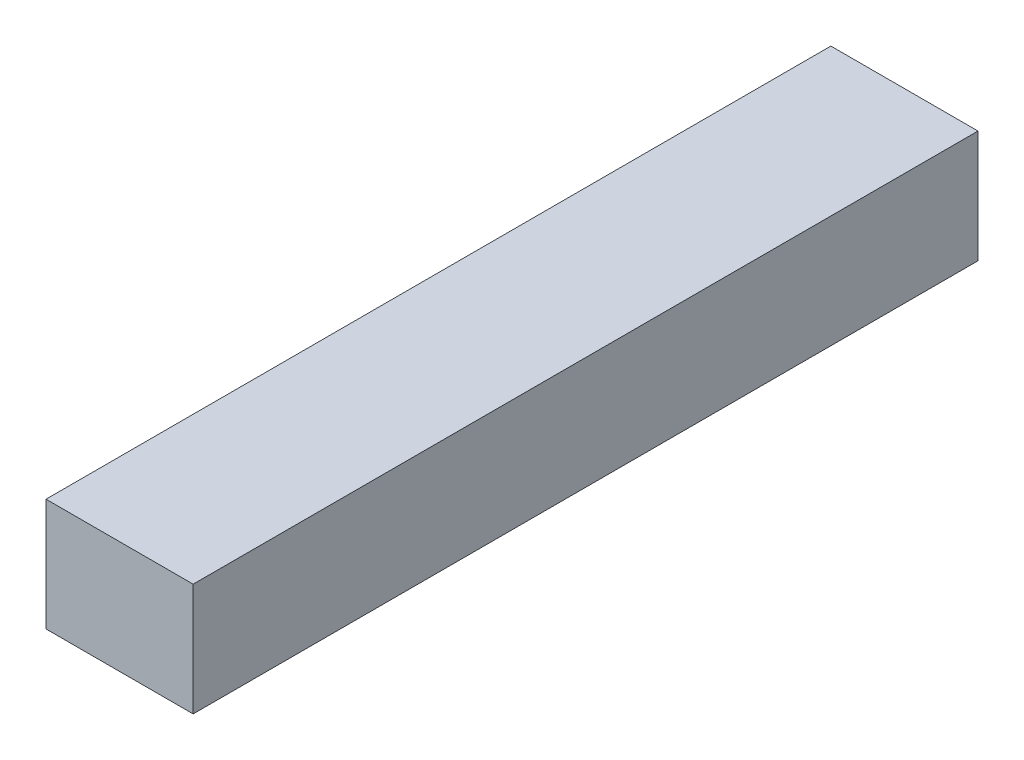
SolidWorks part; units mm, degrees
ref_plane "Front Plane" through (0, 0, 0) normal (0, 0, 1) x (1, 0, 0)
ref_plane "Top Plane" through (0, 0, 0) normal (0, 1, 0) x (1, 0, 0)
ref_plane "Right Plane" through (0, 0, 0) normal (1, 0, 0) x (0, 0, -1)
sketch "Sketch2" plane through (0, 0, 0) normal (0, 0, 1) x (1, 0, 0)
  line L0 (0, 0) -> (0, -4.583)
  line L1 (0, -4.583) -> (6, -4.583)
  line L2 (6, -4.583) -> (6, 0)
  line L3 (6, 0) -> (0, 0)
  dimension "D1" = 4.583
  dimension "D2" = 6
extrude "Boss-Extrude1" add sketch "Sketch2" along normal blind 32
